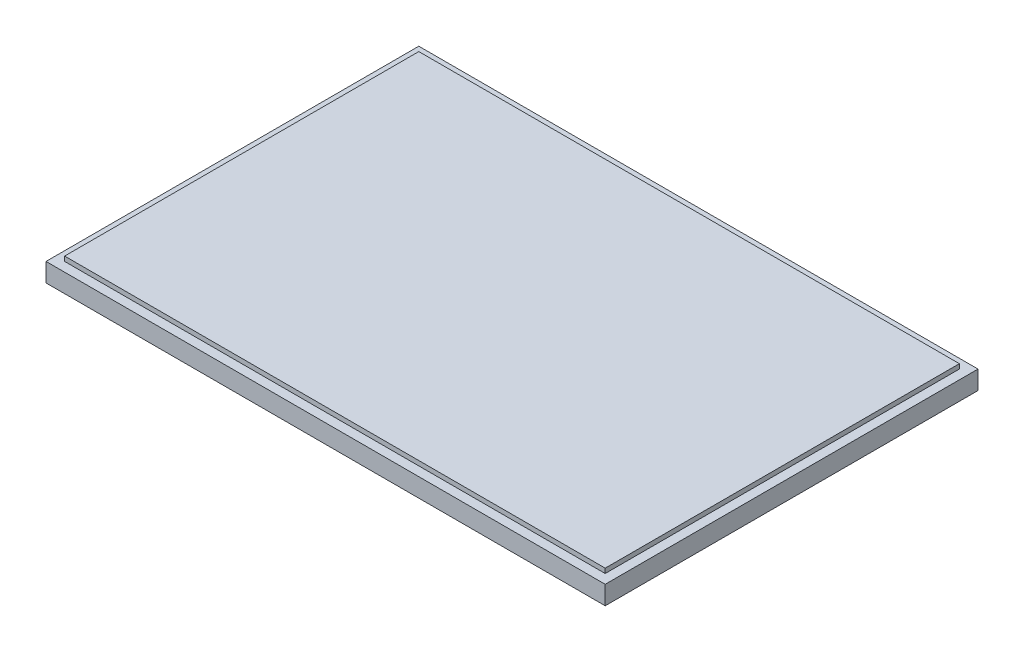
SolidWorks part; units mm, degrees
ref_plane "Front Plane" through (0, 0, 0) normal (0, 0, 1) x (1, 0, 0)
ref_plane "Top Plane" through (0, 0, 0) normal (0, 1, 0) x (1, 0, 0)
ref_plane "Right Plane" through (0, 0, 0) normal (1, 0, 0) x (0, 0, -1)
sketch "Croquis1" plane through (0, 0, 0) normal (0, 1, 0) x (1, 0, 0)
  line L1 (-30, 20) -> (30, 20)
  line L2 (-30, 20) -> (-30, -20)
  line L3 (-30, -20) -> (30, -20)
  line L4 (30, 20) -> (30, -20)
  line L5 (-30, 20) -> (30, -20) construction
  line L6 (-30, -20) -> (30, 20) construction
  point P0 (0, 0)
  dimension "D1" = 60
  dimension "D2" = 40
extrude "Saliente-Extruir1" add sketch "Croquis1" along normal blind 2
sketch "Croquis2" plane through (0, 2, 0) normal (0, 1, 0) x (1, 0, 0)
  line L0 (30, 20) -> (-30, 20) construction
  line L1 (-29, 19) -> (29, 19)
  line L2 (-29, 19) -> (-29, -19)
  line L3 (-29, -19) -> (29, -19)
  line L4 (29, 19) -> (29, -19)
  line L5 (-29, 19) -> (29, -19) construction
  line L6 (-29, -19) -> (29, 19) construction
  line L7 (-30, 20) -> (-30, -20) construction
  point P0 (0, 0)
  dimension "D1" = 1
  dimension "D2" = 1
extrude "Saliente-Extruir2" add sketch "Croquis2" along normal blind 0.5
